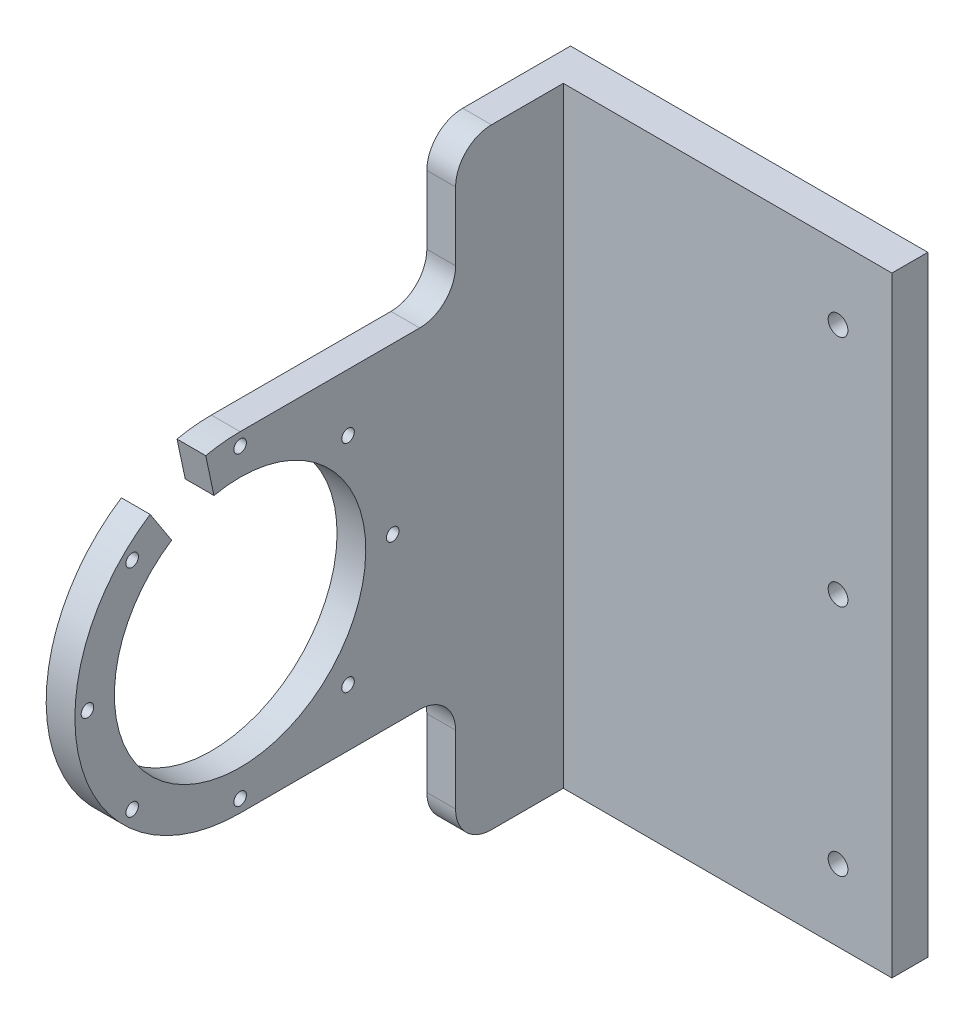
SolidWorks part; units mm, degrees
material "6061 合金"
ref_plane "前视基准面" through (0, 0, 0) normal (0, 0, 1) x (1, 0, 0)
ref_plane "上视基准面" through (0, 0, 0) normal (0, 1, 0) x (1, 0, 0)
ref_plane "右视基准面" through (0, 0, 0) normal (1, 0, 0) x (0, 0, -1)
other "Configuration Table"
sketch "草图1" plane through (0, 0, 0) normal (0, 1, 0) x (1, 0, 0)
  line L0 (0, 0) -> (111.3, 0) construction
  line L1 (111.3, 0) -> (111.3, -10) construction
  line L2 (111.3, -10) -> (8, -10) construction
  line L3 (8, -10) -> (8, -300)
  line L4 (8, -300) -> (0, -300)
  line L5 (0, -300) -> (0, 0)
  line L6 (8, -10) -> (8, 0)
  line L7 (0, 0) -> (8, 0)
  dimension "D1" = 103.3
  dimension "D2" = 290
  dimension "D3" = 10
  dimension "D4" = 8
extrude "凸台-拉伸1" add sketch "草图1" along normal blind 170
sketch "草图2" plane through (8, 0, 0) normal (1, 0, 0) x (0, 0, -1)
  line L0 (-318.0541, 85) -> (-40.874, 85) construction
  line L1 (-300, 170) -> (0, 170) construction
  line L2 (-300, 0) -> (0, 0) construction
  line L7 (0, 170) -> (0, 0) construction
  line L9 (-100, 131) -> (-40, 131)
  line L10 (-40, 131) -> (-40, 170)
  line L11 (-300, 170) -> (0, 170) construction
  line L12 (-100, 39) -> (-40, 39)
  line L13 (-40, 39) -> (-40, 0)
  line L14 (-40, 170) -> (-300, 170)
  line L15 (-300, 170) -> (-300, 0)
  line L16 (-300, 0) -> (-40, 0)
  arc A0 (-100, 131) -> (-100, 39) centre (-100, 85) ccw
  circle A1 centre (-100, 85) radius 35
  dimension "D2" = 70
  dimension "D3" = 46
  dimension "D1" = 100
  dimension "D4" = 40
extrude "切除-拉伸1" cut sketch "草图2" against normal blind 180
sketch "草图5" plane through (8, 0, 0) normal (1, 0, 0) x (0, 0, -1)
  line L0 (-40, 170) -> (0, 170) construction
  line L1 (0, 0) -> (-10, 0)
  line L2 (0, 0) -> (0, 170)
  line L3 (0, 170) -> (-10, 170)
  line L4 (-10, 0) -> (-10, 170)
  dimension "D1" = 10
extrude "凸台-拉伸3" add sketch "草图5" along normal blind 101.5
other "移动面1" [suppressed] parameters "D1"=15
sketch "草图6" plane through (0, 0, 0) normal (0, 0, -1) x (-1, 0, 0)
  line L0 (-109.5, 0) -> (-109.5, 170) construction
  line L1 (-109.5, 0) -> (-109.5, 170) construction
  line L2 (-109.5, 170) -> (0, 170) construction
  line L3 (-109.5, 0) -> (0, 0) construction
  circle A0 centre (-84.5, 150) radius 2.75
  circle A1 centre (-84.5, 20) radius 2.75
  circle A2 centre (-84.5, 85) radius 2.75
  dimension "D1" = 5.5
  dimension "D2" = 25
  dimension "D3" = 20
  dimension "D4" = 20
  dimension "D5" = 65
extrude "切除-拉伸3" cut sketch "草图6" against normal blind 52
sketch "草图8" plane through (0, 0, 0) normal (-1, 0, 0) x (0, 0, 1)
  line L3 (0, 0) -> (40, 0)
  line L4 (40, 170) -> (0, 170)
  line L5 (0, 170) -> (0, 0)
  line L6 (0, 0) -> (40, 0) construction
  line L7 (40, 170) -> (0, 170) construction
  line L8 (0, 170) -> (0, 0) construction
  line L13 (40, 0) -> (40, 39)
  line L14 (40, 0) -> (40, 39)
  line L15 (40, 39) -> (100, 39)
  line L16 (40, 39) -> (100, 39)
  line L17 (100, 131) -> (40, 131)
  line L18 (100, 131) -> (40, 131)
  line L19 (40, 131) -> (40, 170)
  line L20 (40, 131) -> (40, 170)
  arc A0 (58.008, 157.6182) -> (53.4765, 159.7313) centre (55.7423, 158.6748) ccw construction
  arc A1 (100, 39) -> (100, 131) centre (100, 85) ccw
  arc A2 (100, 39) -> (100, 131) centre (100, 85) ccw construction
  arc A3 (58.008, 157.6182) -> (53.4765, 159.7313) centre (55.7423, 158.6748) ccw construction
  arc A4 (30.2194, 143.4465) -> (34.751, 141.3335) centre (32.4852, 142.39) ccw construction
  arc A5 (6.8011, 93.2258) -> (11.3327, 91.1128) centre (9.0669, 92.1693) ccw construction
  arc A6 (9.2756, 64.9423) -> (13.8072, 62.8292) centre (11.5414, 63.8857) ccw construction
  arc A7 (14.0595, 51.7988) -> (18.591, 49.6857) centre (16.3252, 50.7423) ccw construction
  arc A8 (30.3442, 28.5418) -> (34.8758, 26.4287) centre (32.61, 27.4852) ccw construction
  arc A9 (80.5649, 5.1235) -> (85.0965, 3.0104) centre (82.8307, 4.0669) ccw construction
  arc A10 (113.38, 5.4849) -> (108.8485, 7.598) centre (111.1143, 6.5414) ccw construction
  arc A11 (126.5235, 10.2687) -> (121.992, 12.3818) centre (124.2577, 11.3252) ccw construction
  arc A12 (149.7806, 26.5535) -> (145.249, 28.6665) centre (147.5148, 27.61) ccw construction
  arc A13 (173.1989, 76.7742) -> (168.6673, 78.8872) centre (170.9331, 77.8307) ccw construction
  arc A14 (170.7244, 105.0577) -> (166.1928, 107.1708) centre (168.4586, 106.1143) ccw construction
  arc A15 (165.9405, 118.2012) -> (161.409, 120.3143) centre (163.6748, 119.2577) ccw construction
  arc A16 (149.6558, 141.4582) -> (145.1242, 143.5713) centre (147.39, 142.5148) ccw construction
  arc A17 (99.4351, 164.8765) -> (94.9035, 166.9896) centre (97.1693, 165.9331) ccw construction
  arc A18 (58.008, 157.6182) -> (53.4765, 159.7313) centre (55.7423, 158.6748) ccw construction
  arc A19 (30.2194, 143.4465) -> (34.751, 141.3335) centre (32.4852, 142.39) ccw construction
  arc A20 (6.8011, 93.2258) -> (11.3327, 91.1128) centre (9.0669, 92.1693) ccw construction
  arc A21 (9.2756, 64.9423) -> (13.8072, 62.8292) centre (11.5414, 63.8857) ccw construction
  arc A22 (14.0595, 51.7988) -> (18.591, 49.6857) centre (16.3252, 50.7423) ccw construction
  arc A23 (30.3442, 28.5418) -> (34.8758, 26.4287) centre (32.61, 27.4852) ccw construction
  arc A24 (80.5649, 5.1235) -> (85.0965, 3.0104) centre (82.8307, 4.0669) ccw construction
  arc A25 (113.38, 5.4849) -> (108.8485, 7.598) centre (111.1143, 6.5414) ccw construction
  arc A26 (126.5235, 10.2687) -> (121.992, 12.3818) centre (124.2577, 11.3252) ccw construction
  arc A27 (149.7806, 26.5535) -> (145.249, 28.6665) centre (147.5148, 27.61) ccw construction
  arc A28 (173.1989, 76.7742) -> (168.6673, 78.8872) centre (170.9331, 77.8307) ccw construction
  arc A29 (170.7244, 105.0577) -> (166.1928, 107.1708) centre (168.4586, 106.1143) ccw construction
  arc A30 (165.9405, 118.2012) -> (161.409, 120.3143) centre (163.6748, 119.2577) ccw construction
  arc A31 (149.6558, 141.4582) -> (145.1242, 143.5713) centre (147.39, 142.5148) ccw construction
  arc A32 (99.4351, 164.8765) -> (94.9035, 166.9896) centre (97.1693, 165.9331) ccw construction
  circle A33 centre (55.7423, 158.6748) radius 2.5
  circle A34 centre (97.1693, 165.9331) radius 2.5
  circle A35 centre (147.39, 142.5148) radius 2.5
  circle A36 centre (163.6748, 119.2577) radius 2.5
  circle A37 centre (168.4586, 106.1143) radius 2.5
  circle A38 centre (170.9331, 77.8307) radius 2.5
  circle A39 centre (147.5148, 27.61) radius 2.5
  circle A40 centre (124.2577, 11.3252) radius 2.5
  circle A41 centre (111.1143, 6.5414) radius 2.5
  circle A42 centre (82.8307, 4.0669) radius 2.5
  circle A43 centre (32.61, 27.4852) radius 2.5
  circle A44 centre (16.3252, 50.7423) radius 2.5
  circle A45 centre (11.5414, 63.8857) radius 2.5
  circle A46 centre (9.0669, 92.1693) radius 2.5
  circle A47 centre (32.4852, 142.39) radius 2.5
  dimension "D1" = 0
extrude "切除-拉伸4" [suppressed] cut sketch "草图8" against normal blind 52 contours A47 | A34 | A35 | A36 | A37 | A38 | A39 | A40 | A41 | A42 | A43 | A33
fillet "圆角2" radius 10 4 edges at (4, 170, 40) (4, 131, 40) (4, 0, 40) (4, 39, 40)
sketch "草图11" plane through (0, 0, 0) normal (-1, 0, 0) x (0, 0, 1)
  line L0 (100, 140.5507) -> (100, 30.313) construction
  circle A0 centre (100, 85) radius 35 construction
  circle A1 centre (100, 85) radius 35 construction
  circle A3 centre (100, 42.5) radius 1.75
  circle A4 centre (69.948, 54.948) radius 1.75
  circle A5 centre (57.5, 85) radius 1.75
  circle A6 centre (69.948, 115.052) radius 1.75
  circle A7 centre (100, 127.5) radius 1.75
  circle A8 centre (130.052, 115.052) radius 1.75
  circle A9 centre (142.5, 85) radius 1.75
  circle A10 centre (130.052, 54.948) radius 1.75
  point P23 (100, 85)
  dimension "D1" = 3.5
  dimension "D2" = 42.5
  dimension "D3" = 8
extrude "切除-拉伸5" cut sketch "草图11" against normal blind 10 contours A10 | A3 | A6 | A7 | A8 | A9 | A4 | A5
sketch "草图12" plane through (0, 0, 0) normal (-1, 0, 0) x (0, 0, 1)
  line L0 (100, 85) -> (110.3956, 133.9074)
  line L1 (100, 85) -> (127.232, 126.9335)
  line L2 (100, 85) -> (130.052, 115.052) construction
  line L3 (100, 85) -> (100, 127.5) construction
  arc A0 (110.3956, 133.9074) -> (127.232, 126.9335) centre (100, 85) cw
  dimension "D1" = 12
  dimension "D2" = 12
  dimension "D3" = 50
extrude "切除-拉伸6" cut sketch "草图12" against normal blind 13 contours A0 L1 L0
other "移动面2" face at (109.5, 85, 5) parameters "D1"=10
